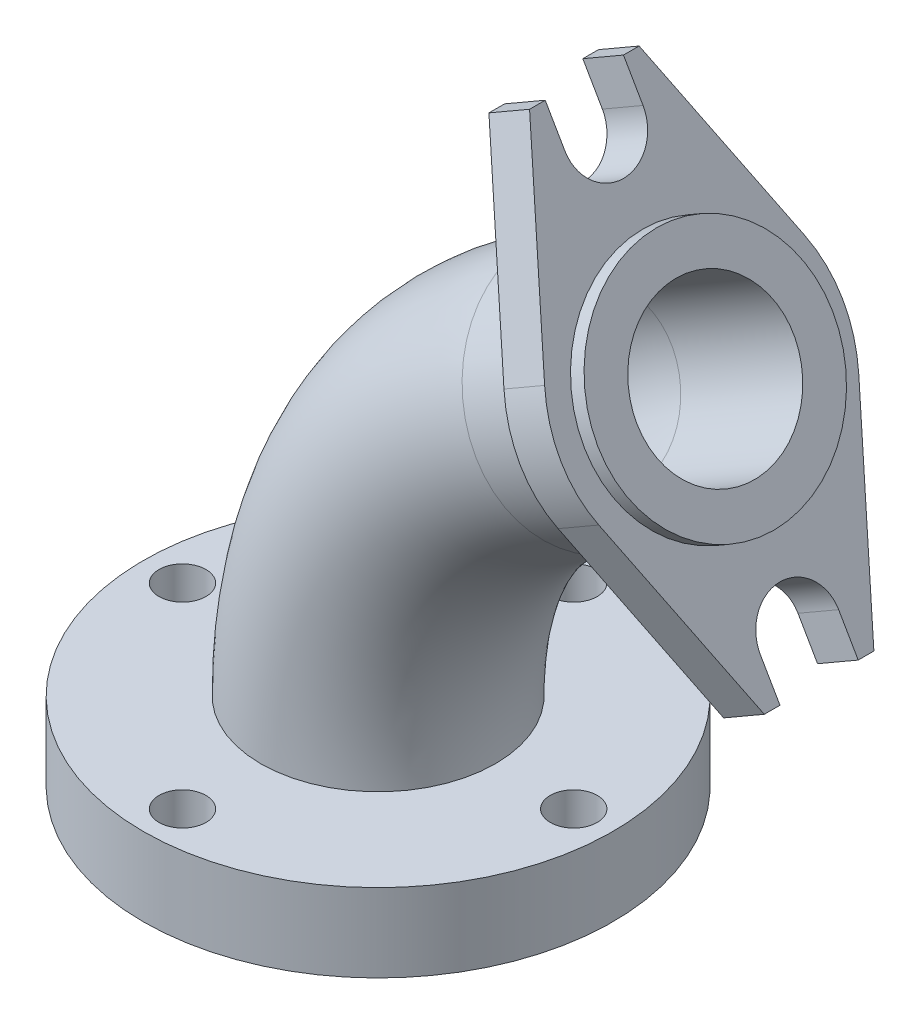
SolidWorks part; units mm, degrees
ref_plane "前视基准面" through (0, 0, 0) normal (0, 0, 1) x (1, 0, 0)
ref_plane "上视基准面" through (0, 0, 0) normal (0, 1, 0) x (1, 0, 0)
ref_plane "右视基准面" through (0, 0, 0) normal (1, 0, 0) x (0, 0, -1)
other "Configuration Table"
sketch "草图1" plane through (0, 0, 0) normal (0, 1, 0) x (1, 0, 0)
  line L0 (-37.5211, 0) -> (35.3505, 0) construction
  line L1 (0, 31.371) -> (0, -28.4768) construction
  circle A0 centre (0, 0) radius 25 construction
  circle A1 centre (0, 0) radius 30
  circle A2 centre (0, 0) radius 10
  circle A3 centre (25, 0) radius 3
  circle A4 centre (0, -25) radius 3
  circle A5 centre (-25, 0) radius 3
  circle A6 centre (0, 25) radius 3
  point P20 (0, 0)
  dimension "D1" = 50
  dimension "D2" = 60
  dimension "D3" = 20
  dimension "D4" = 6
  dimension "D5" = 4
extrude "凸台-拉伸1" add sketch "草图1" along normal blind 10
sketch "草图2" plane through (0, 10, 0) normal (0, 1, 0) x (1, 0, 0)
  circle A0 centre (0, 0) radius 10 construction
  circle A1 centre (0, 0) radius 10
  circle A2 centre (0, 0) radius 15
  dimension "D1" = 30
sketch "草图3" plane through (0, 0, 0) normal (0, 0, 1) x (1, 0, 0)
  line L0 (0, 10) -> (55, 10) construction
  line L1 (15, 10) -> (-15, 10) construction
  line L2 (55, 10) -> (21.884, 67.3586) construction
  line L3 (27.5, 57.6314) -> (43.0885, 66.6314)
  arc A0 (0, 10) -> (27.5, 57.6314) centre (55, 10) cw
  dimension "D2" = 55
  dimension "D1" = 60
  dimension "D3" = 18
sweep "扫描1" add profiles "草图2" path "草图3"
ref_plane "基准面1" through (59.4365, 34.3157, 0) normal (0.866, 0.5, 0) x (0, 0, -1)
sketch "草图5" plane through (59.4365, 34.3157, 0) normal (0.866, 0.5, 0) x (0, 0, -1)
  line L0 (0, 92.4771) -> (0, -30.9919) construction
  line L1 (-122.7143, 36.1603) -> (-19.5, 36.1603) construction
  line L2 (-7, 6.1603) -> (-5, 6.1603)
  line L3 (7, 6.1603) -> (16.6154, 29.2372)
  line L4 (16.6154, 43.0833) -> (7, 66.1603)
  line L5 (7, 66.1603) -> (5, 66.1603)
  line L6 (-7, 66.1603) -> (-16.6154, 43.0833)
  line L7 (-16.6154, 29.2372) -> (-7, 6.1603)
  line L8 (5, 61.1603) -> (5, 66.1603)
  line L9 (-5, 61.1603) -> (-5, 66.1603)
  line L10 (-5, 11.1603) -> (-5, 6.1603)
  line L11 (5, 11.1603) -> (5, 6.1603)
  line L12 (-5, 66.1603) -> (-7, 66.1603)
  line L13 (5, 6.1603) -> (7, 6.1603)
  line L14 (-18, 36.1603) -> (126.4878, 36.1603) construction
  arc A1 (-16.6154, 43.0833) -> (-16.6154, 29.2372) centre (0, 36.1603) ccw
  circle A2 centre (0, 36.1603) radius 10 construction
  circle A3 centre (0, 36.1603) radius 10
  arc A4 (-5, 61.1603) -> (5, 61.1603) centre (0, 61.1603) ccw
  arc A5 (-5, 11.1603) -> (5, 11.1603) centre (0, 11.1603) cw
  arc A6 (16.6154, 29.2372) -> (16.6154, 43.0833) centre (0, 36.1603) ccw
  dimension "D3" = 36
  dimension "D4" = 10
  dimension "D1" = 14
  dimension "D2" = 60
  dimension "D5" = 50
extrude "凸台-拉伸2" add sketch "草图5" against normal blind 6
